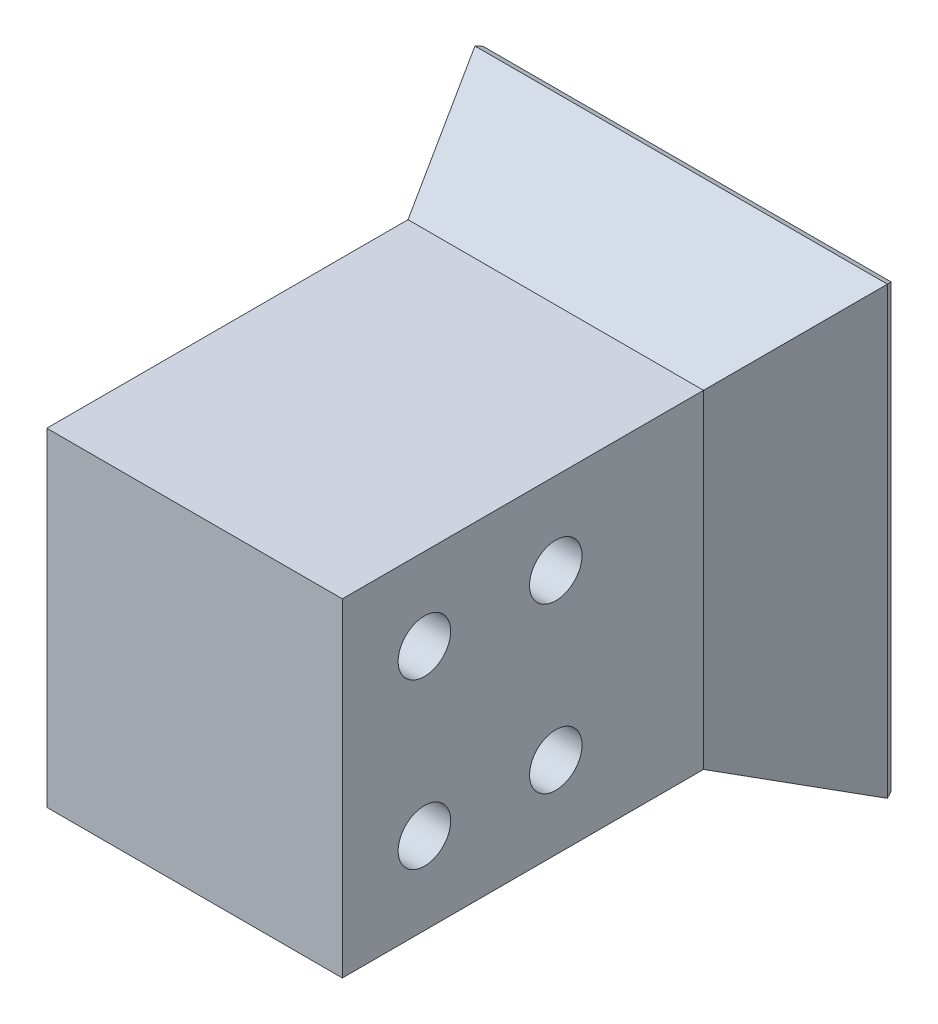
SolidWorks part; units mm, degrees
ref_plane "Front Plane" through (0, 0, 0) normal (0, 0, 1) x (1, 0, 0)
ref_plane "Top Plane" through (0, 0, 0) normal (0, 1, 0) x (1, 0, 0)
ref_plane "Right Plane" through (0, 0, 0) normal (1, 0, 0) x (0, 0, -1)
sketch "Sketch2" plane through (0, 0, 0) normal (0, 0, 1) x (1, 0, 0)
  line L1 (-9, 10) -> (9, 10)
  line L2 (-9, 10) -> (-9, -10)
  line L3 (-9, -10) -> (9, -10)
  line L4 (9, 10) -> (9, -10)
  line L5 (-9, 10) -> (9, -10) construction
  line L6 (-9, -10) -> (9, 10) construction
  point P0 (0, 0)
  dimension "D1" = 18
  dimension "D2" = 20
extrude "Boss-Extrude1" add sketch "Sketch2" along normal blind 22
sketch "Sketch3" plane through (0, 0, 0) normal (0, 0, -1) x (-1, 0, 0)
  line L4 (-9, 10) -> (-9, -10)
  line L5 (-9, -10) -> (9, -10)
  line L6 (9, -10) -> (9, 10)
  line L7 (9, 10) -> (-9, 10)
  line L8 (-9, 10) -> (-9, -10)
  line L9 (-9, -10) -> (9, -10)
  line L10 (9, -10) -> (9, 10)
  line L11 (9, 10) -> (-9, 10)
  dimension "D1" = 0
extrude "Boss-Extrude2" add sketch "Sketch3" along normal blind 8 draft 25 draft outward yes
sketch "Sketch4" plane through (9, 0, 0) normal (1, 0, 0) x (0, 0, -1)
  line L0 (-22, -10) -> (-22, 10) construction
  line L1 (-22, 10) -> (0, 10) construction
  circle A0 centre (-17, 5) radius 1.6
  circle A1 centre (-9, 5) radius 1.6
  circle A2 centre (-17, -5) radius 1.6
  circle A3 centre (-9, -5) radius 1.6
  point P12 (0, 0)
  point P13 (0, 0)
  point P14 (0, 0)
  point P15 (0, 0)
  dimension "D1" = 3.2
  dimension "D2" = 3.2
  dimension "D3" = 3.2
  dimension "D4" = 3.2
  dimension "D5" = 5
  dimension "D6" = 8
  dimension "D8" = 10
  dimension "D7" = 5
extrude "Cut-Extrude1" cut sketch "Sketch4" against normal up to surface (18 mm away) up to face at (-9, 0, 11)
chamfer "Chamfer1" distance 0.4 angle 45 4 edges at (0, -13.7305, -8) (-12.7305, 0, -8) (0, 13.7305, -8) (12.7305, 0, -8)
